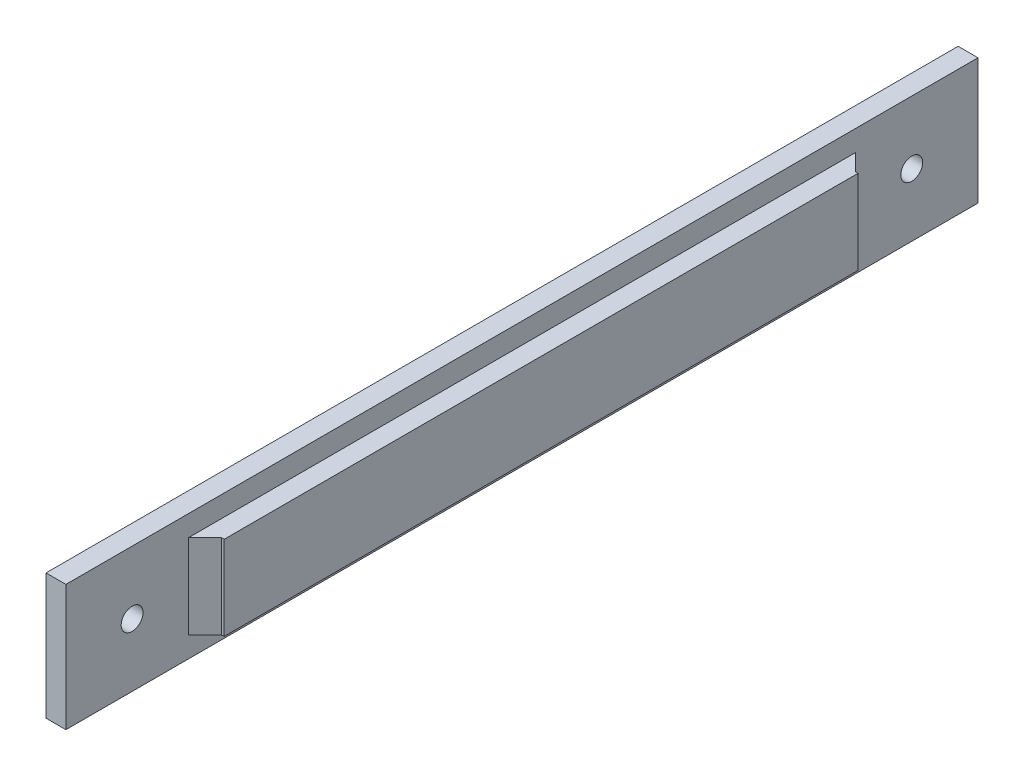
SolidWorks part; units mm, degrees
ref_plane "前视基准面" through (0, 0, 0) normal (0, 0, 1) x (1, 0, 0)
ref_plane "上视基准面" through (0, 0, 0) normal (0, 1, 0) x (1, 0, 0)
ref_plane "右视基准面" through (0, 0, 0) normal (1, 0, 0) x (0, 0, -1)
sketch "草图1" plane through (0, 0, 0) normal (0, 0, 1) x (1, 0, 0)
  line L1 (0, 0) -> (13, 0)
  line L2 (0, 0) -> (0, 13)
  line L3 (0, 13) -> (13, 13)
  line L4 (13, 0) -> (13, 13)
  dimension "D1" = 13
  dimension "D2" = 13
extrude "拉伸-薄壁1" add sketch "草图1" along normal blind 137.7 thin
sketch "草图2" plane through (-3, 0, 0) normal (-1, 0, 0) x (0, 0, 1)
  line L0 (0, 16) -> (0, -3) construction
  line L1 (137.7, 16) -> (137.7, -3) construction
  circle A0 centre (10, 6.5) radius 1.65
  circle A1 centre (127.7, 6.5) radius 1.65
  dimension "D1" = 3.3
  dimension "D2" = 3.3
  dimension "D3" = 10
  dimension "D4" = 10
extrude "切除-拉伸1" cut sketch "草图2" against normal blind 30
sketch "草图3" plane through (16, 0, 0) normal (1, 0, 0) x (0, 0, -1)
  line L1 (-137.7, 16) -> (0, 16)
  line L2 (-137.7, 16) -> (-137.7, -3)
  line L3 (-137.7, -3) -> (0, -3)
  line L4 (0, 16) -> (0, -3)
extrude "切除-拉伸2" cut sketch "草图3" against normal blind 16
sketch "草图4" plane through (0, 0, 0) normal (1, 0, 0) x (0, 0, -1)
  line L0 (0, 16) -> (0, -3) construction
  line L1 (-116.7, 12.85) -> (-21, 12.85)
  line L2 (-116.7, 12.85) -> (-116.7, 0.15)
  line L3 (-116.7, 0.15) -> (-21, 0.15)
  line L4 (-21, 12.85) -> (-21, 0.15)
  line L5 (-137.7, 16) -> (-137.7, -3) construction
  line L6 (-137.7, -3) -> (0, -3) construction
  line L7 (0, 16) -> (-137.7, 16) construction
  point P8 (-21, 6.5)
  dimension "D1" = 21
  dimension "D2" = 21
  dimension "D3" = 12.7
  dimension "D4" = 9.5
  dimension "D5" = 3.15
  dimension "D6" = 3.15
extrude "凸台-拉伸1" add sketch "草图4" along normal blind 2.9
chamfer "倒角1" distance 2.5 angle 45 2 edges at (0, 6.5, 21) (0, 6.5, 116.7)
